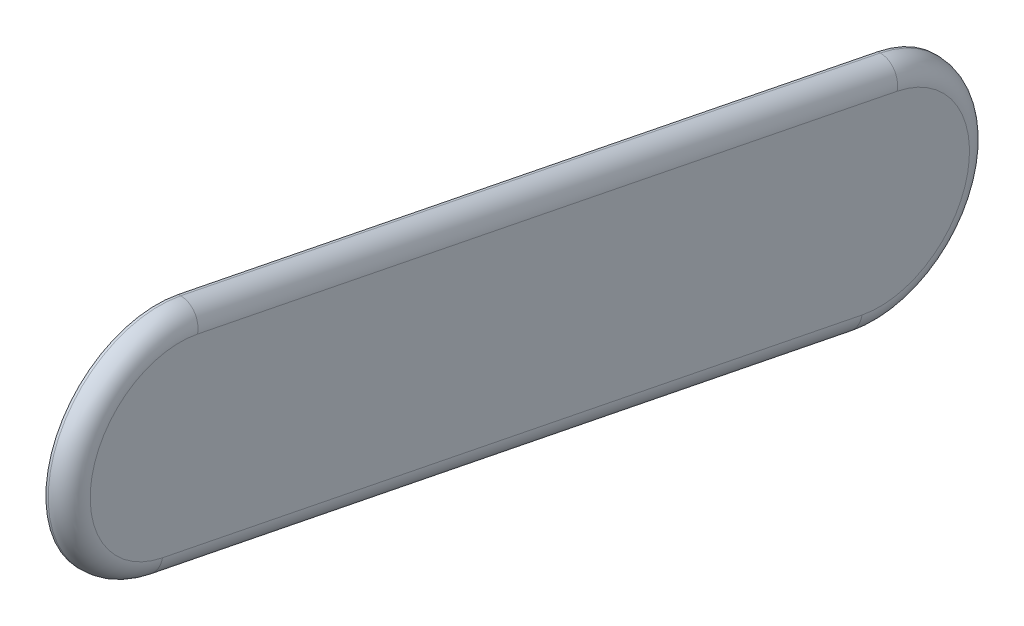
SolidWorks part; units mm, degrees
ref_plane "Front Plane" through (0, 0, 0) normal (0, 0, 1) x (1, 0, 0)
ref_plane "Top Plane" through (0, 0, 0) normal (0, 1, 0) x (1, 0, 0)
ref_plane "Right Plane" through (0, 0, 0) normal (1, 0, 0) x (0, 0, -1)
sketch "Sketch1" plane through (0, 0, 0) normal (1, 0, 0) x (0, 0, -1)
  line L0 (-104.155, 59.6611) -> (-27.955, 44.4645) construction
  line L1 (-101.794, 71.5002) -> (-25.594, 56.3036)
  line L2 (-106.5161, 47.8219) -> (-30.3161, 32.6254)
  arc A0 (-101.794, 71.5002) -> (-106.5161, 47.8219) centre (-104.155, 59.6611) ccw
  arc A1 (-30.3161, 32.6254) -> (-25.594, 56.3036) centre (-27.955, 44.4645) ccw
  point P2 (-66.055, 52.0628)
  dimension "D1" = 76.2
extrude "Boss-Extrude2" add sketch "Sketch1" along normal blind 2.54
fillet "Fillet1" radius 2.286 4 edges at (2.54, 63.9019, 63.694) (2.54, 42.1034, 16.1159) (2.54, 40.2237, 68.4161) (2.54, 62.0221, 115.9942)
